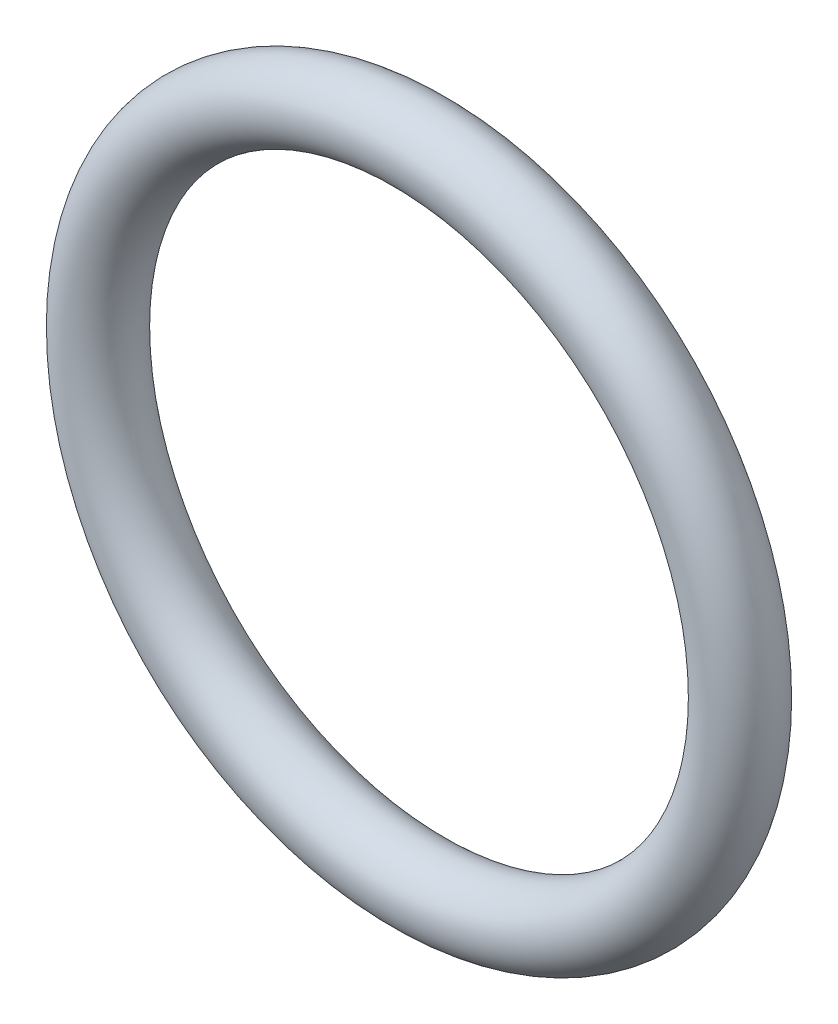
SolidWorks part; units mm, degrees
material "BUTYL"
ref_plane "Plan de face" through (0, 0, 0) normal (0, 0, 1) x (1, 0, 0)
ref_plane "Plan de dessus" through (0, 0, 0) normal (0, 1, 0) x (1, 0, 0)
ref_plane "Plan de droite" through (0, 0, 0) normal (1, 0, 0) x (0, 0, -1)
sketch "Esquisse1" plane through (0, 0, 0) normal (1, 0, 0) x (0, 0, -1)
  circle A0 centre (0, 0) radius 1.65
  dimension "D1" = 3.3
sketch "Esquisse2" plane through (0, 0, 0) normal (0, 0, 1) x (1, 0, 0)
  circle A0 centre (0, 14.5) radius 14.5
  dimension "D1" = 29
sweep "Balayage1" add profiles "Esquisse1" path "Esquisse2"
sketch "Esquisse3" plane through (0, 0, 0) normal (0, 0, 1) x (1, 0, 0)
  circle A0 centre (0, 14.5) radius 14.5 construction
  dimension "D1" = 29
